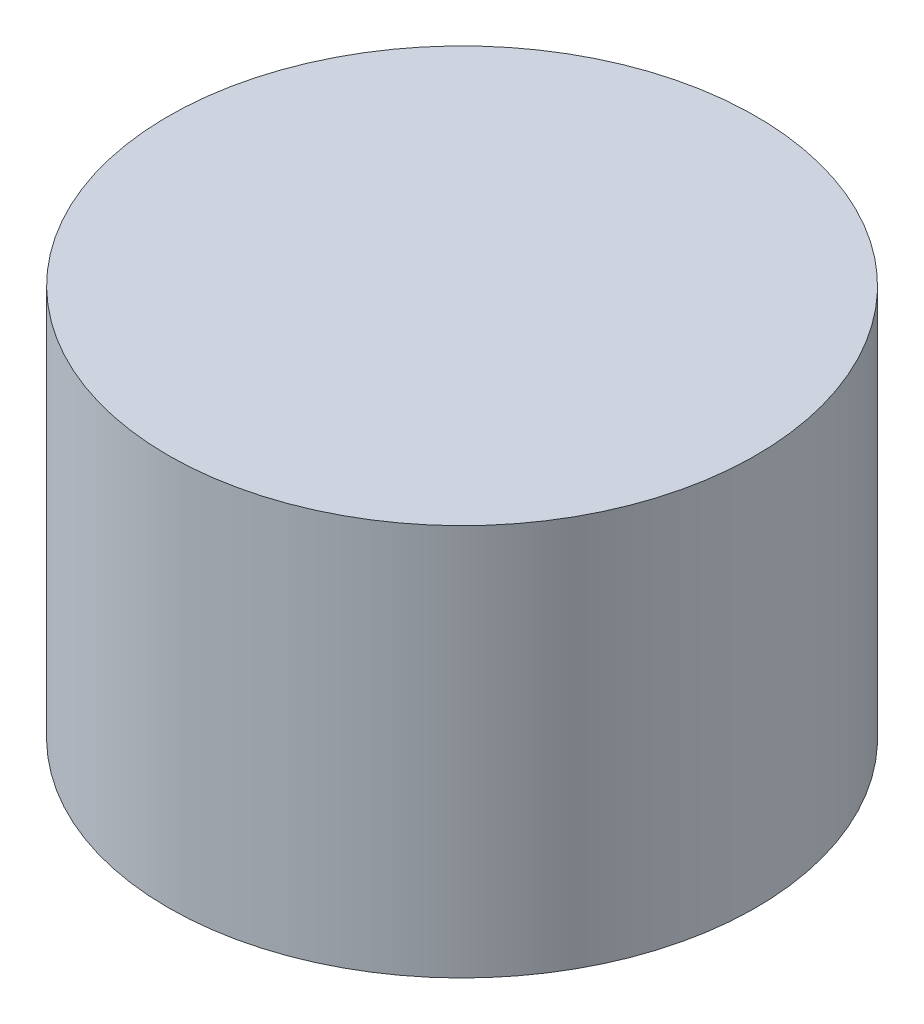
SolidWorks part; units mm, degrees
ref_plane "Front Plane" through (0, 0, 0) normal (0, 0, 1) x (1, 0, 0)
ref_plane "Top Plane" through (0, 0, 0) normal (0, 1, 0) x (1, 0, 0)
ref_plane "Right Plane" through (0, 0, 0) normal (1, 0, 0) x (0, 0, -1)
sketch "Sketch1" plane through (0, 0, 0) normal (0, 1, 0) x (1, 0, 0)
  circle A0 centre (0, 0) radius 76.2
  dimension "D1" = 152.4
extrude "Boss-Extrude1" add sketch "Sketch1" along normal mid plane 101.6
